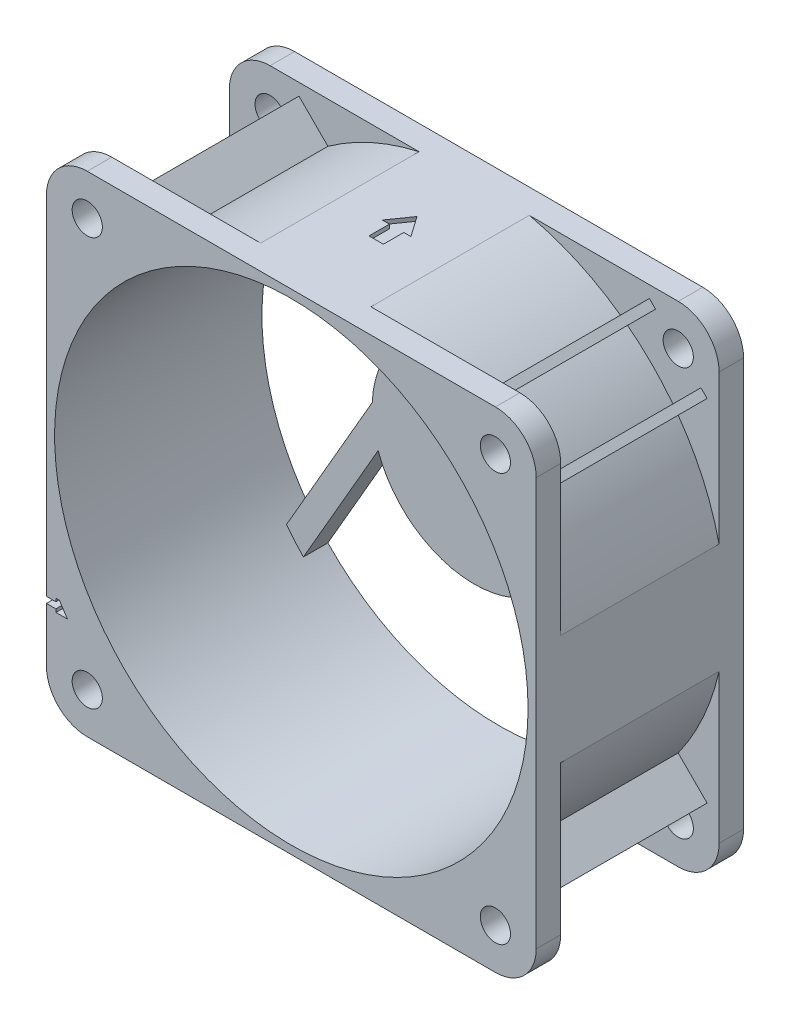
SolidWorks part; units mm, degrees
ref_plane "Front" through (0, 0, 0) normal (0, 0, 1) x (1, 0, 0)
ref_plane "Top" through (0, 0, 0) normal (0, 1, 0) x (1, 0, 0)
ref_plane "Right" through (0, 0, 0) normal (1, 0, 0) x (0, 0, -1)
sketch "Support-Front" plane through (0, 0, 0) normal (0, 0, 1) x (1, 0, 0)
  line L0 (-30, 0) -> (30, 0) construction
  line L1 (0, 30) -> (0, -30) construction
  line L2 (30, -25) -> (30, 25)
  line L3 (-30, -25) -> (-30, 25)
  line L4 (25, 30) -> (-25, 30)
  line L5 (25, -30) -> (-25, -30)
  line L6 (0, 30) -> (0, 40.3553) construction
  arc A0 (30, 25) -> (25, 30) centre (25, 25) ccw
  arc A1 (-30, 25) -> (-25, 30) centre (-25, 25) cw
  arc A2 (-30, -25) -> (-25, -30) centre (-25, -25) ccw
  arc A3 (30, -25) -> (25, -30) centre (25, -25) cw
  circle A4 centre (25, 25) radius 1.85
  circle A5 centre (-25, 25) radius 1.85
  circle A6 centre (-25, -25) radius 1.85
  circle A7 centre (25, -25) radius 1.85
  circle A8 centre (0, 0) radius 29
  circle A9 centre (0, 0) radius 12.5
  circle A10 centre (0, 0) radius 30
  circle A11 centre (0, 0) radius 40.3553 construction
  dimension "Diam-Fixing-Hole" = 3.7
  dimension "Diam-Fan-Hole" = 58
  dimension "Diam-Fixing-Plate-Fan" = 25
  dimension "Width" = 60
  dimension "Dist-Fixing-Hole" = 50
sketch "Support-Right" plane through (0, 0, 0) normal (1, 0, 0) x (0, 0, -1)
  line L0 (-25.4, 0) -> (0, 0) construction
  line L1 (-12.7, 30) -> (-12.7, -30) construction
  line L2 (-3, 30) -> (-3, -30)
  line L3 (-25.4, 30) -> (0, 30)
  line L4 (-25.4, 30) -> (-25.4, -30)
  line L5 (-25.4, -30) -> (0, -30)
  line L6 (0, 30) -> (0, -30)
  line L7 (-22.4, 30) -> (-22.4, -30)
  line L8 (-12.7, 30) -> (-12.7, 31.5) construction
  line L9 (0, 0) -> (-1.5, 0) construction
  line L10 (-1.5, 0) -> (-3, 0) construction
  dimension "Thickness" = 25.4
sketch "Support-Front-Reinforcment-Place" plane through (0, 0, 0) normal (0, 0, 1) x (1, 0, 0)
  line L0 (0, 30) -> (0, 0) construction
  line L1 (0, 29) -> (0, 30) construction
  line L2 (9.459, 30) -> (9.9454, 27.2413)
  line L3 (25, 30) -> (-25, 30) construction
  line L4 (-9.459, 30) -> (-9.9454, 27.2413)
  line L5 (9.459, 30) -> (0, 0) construction
  line L6 (-9.459, 30) -> (0, 0) construction
  line L7 (9.459, 30) -> (-9.459, 30)
  circle A3 centre (0, 0) radius 29 construction
  arc A4 (9.9454, 27.2413) -> (-9.9454, 27.2413) centre (0, 0) ccw
  point P10 (0, 29.5)
  dimension "D1" = 20
  dimension "D2" = 35
sketch "Support-Front-Reinforcment-Strip" plane through (0, 0, 0) normal (0, 0, 1) x (1, 0, 0)
  line L0 (17.381, 24.452) -> (21.4645, 28.5355)
  line L1 (24.452, 17.381) -> (28.5355, 21.4645)
  line L2 (25, 25) -> (0, 0) construction
  line L3 (28.5355, 21.4645) -> (27.7796, 22.2204)
  line L4 (21.4645, 28.5355) -> (22.2204, 27.7796)
  line L5 (27.7796, 22.2204) -> (23.8099, 18.2507)
  line L6 (22.2204, 27.7796) -> (18.2507, 23.8099)
  line L7 (25, 25) -> (23.8099, 18.2507) construction
  line L8 (25, 25) -> (18.2507, 23.8099) construction
  line L9 (29.2915, 20.7085) -> (25.8374, 17.2544)
  line L10 (20.7085, 29.2915) -> (17.2544, 25.8374)
  line L11 (29.2915, 20.7085) -> (29.2915, 10.3584)
  line L12 (20.7085, 29.2915) -> (10.3584, 29.2915)
  line L13 (28.5355, 21.4645) -> (29.2915, 20.7085) construction
  line L14 (21.4645, 28.5355) -> (20.7085, 29.2915) construction
  line L15 (21.9691, 21.9691) -> (21.2132, 21.2132) construction
  line L16 (20.7085, 29.2915) -> (22.2204, 27.7796) construction
  line L17 (-28.8419, -17.5957) -> (-30, -17.5957)
  line L18 (-30, -25) -> (-30, 25) construction
  line L19 (-28.8419, -17.2194) -> (-28.8419, -17.5957)
  line L20 (-28.8419, -17.2194) -> (-28.3997, -17.2194)
  line L21 (-27.4306, -18.7246) -> (-28.8419, -18.7246)
  line L22 (-28.8419, -18.3483) -> (-30, -18.3483)
  line L23 (-28.8419, -18.3483) -> (-28.8419, -18.7246)
  line L24 (-28.8419, -18.3483) -> (-27.6837, -18.3483) construction
  line L25 (-30, -17.972) -> (-25.3435, -17.972) construction
  line L26 (-27.6717, -17.972) -> (-27.6717, -17.5957) construction
  line L27 (-27.6717, -17.972) -> (-27.6717, -18.3483) construction
  line L28 (-28.8419, -18.3483) -> (-30, -17.972) construction
  line L29 (-25, -25) -> (-30, -25) construction
  line L30 (-27.5, -17.972) -> (-27.5, -21.486) construction
  line L31 (-27.5, -17.972) -> (-27.5, -14.458) construction
  line L32 (-27.5, -21.486) -> (-27.5, -25) construction
  line L33 (-25, -25) -> (-23.4846, -23.4846) construction
  line L34 (-23.4846, -23.4846) -> (-21.9691, -21.9691) construction
  arc A0 (21.4645, 28.5355) -> (28.5355, 21.4645) centre (25, 25) cw
  arc A1 (30, 25) -> (25, 30) centre (25, 25) ccw construction
  circle A2 centre (0, 0) radius 31.069
  circle A3 centre (0, 0) radius 30 construction
  circle A4 centre (0, 0) radius 33.2122 construction
  arc A6 (24.452, 17.381) -> (17.381, 24.452) centre (0, 0) ccw
  dimension "D1" = 35
  dimension "D2" = 45
  dimension "D3" = 18
  dimension "D4" = 45
sketch "Support-Front-Bone" plane through (0, 0, 0) normal (0, 0, 1) x (1, 0, 0)
  line L0 (-12.3101, -2.1706) -> (-21.9794, -18.9184) construction
  line L1 (-12.4892, 0.5192) -> (-22.9926, -17.6732)
  line L2 (-11.7643, -4.2252) -> (-20.9201, -20.0836)
  line L3 (0, 0) -> (0, 30) construction
  line L4 (25, 30) -> (-25, 30) construction
  line L6 (0, 0) -> (-12.3101, -2.1706) construction
  circle A0 centre (0, 0) radius 29 construction
  circle A1 centre (0, 0) radius 12.5 construction
  arc A2 (-12.4892, 0.5192) -> (-11.7643, -4.2252) centre (0, 0) ccw
  arc A3 (-22.9926, -17.6732) -> (-20.9201, -20.0836) centre (0, 0) ccw
  dimension "Angle-Bone" = 210
  dimension "Angle-Place-Bone" = 260
sketch "Support-Air-Exhaust" plane through (0, 0, 0) normal (0, 1, 0) x (1, 0, 0)
  line L0 (0, 0) -> (0, -10) construction
  line L1 (0, -10) -> (0, -12.5) construction
  line L2 (0, -12.5) -> (0, -15) construction
  line L3 (0, -15) -> (0, -10) construction
  line L4 (0, -10) -> (-1.7505, -12.5)
  line L5 (-1.7505, -12.5) -> (-0.8816, -12.5)
  line L6 (-0.8816, -12.5) -> (-0.8816, -15)
  line L7 (0.8816, -15) -> (-0.8816, -15)
  line L8 (0, -10) -> (-0.8816, -15) construction
  line L9 (-0.8816, -12.5) -> (0, -12.5) construction
  line L10 (0.8816, -12.5) -> (0.8816, -15)
  line L11 (1.7505, -12.5) -> (0.8816, -12.5)
  line L12 (0, -10) -> (1.7505, -12.5)
  dimension "D1" = 10
  dimension "D2" = 5
  dimension "D3" = 35
  dimension "D4" = 10
ref_plane "Plane1" through (0, 0, 25.4) normal (0, 0, 1) x (1, 0, 0)
ref_plane "Plane2" through (0, 29.5, 0) normal (0, 1, 0) x (-1, 0, 0)
sketch "Sketch-Body" plane through (0, 0, 0) normal (0, 0, 1) x (1, 0, 0)
  line L4 (-25, -30) -> (25, -30)
  line L5 (-30, 25) -> (-30, -25)
  line L6 (25, 30) -> (-25, 30)
  line L7 (30, -25) -> (30, 25)
  line L8 (-25, -30) -> (25, -30)
  line L9 (-30, 25) -> (-30, -25)
  line L10 (25, 30) -> (-25, 30)
  line L11 (30, -25) -> (30, 25)
  circle A0 centre (0, 0) radius 29 construction
  circle A1 centre (0, 0) radius 29
  arc A4 (-30, -25) -> (-25, -30) centre (-25, -25) ccw
  arc A5 (-25, 30) -> (-30, 25) centre (-25, 25) ccw
  arc A6 (30, 25) -> (25, 30) centre (25, 25) ccw
  arc A7 (25, -30) -> (30, -25) centre (25, -25) ccw
  arc A8 (-30, -25) -> (-25, -30) centre (-25, -25) ccw
  arc A9 (-25, 30) -> (-30, 25) centre (-25, 25) ccw
  arc A10 (30, 25) -> (25, 30) centre (25, 25) ccw
  arc A11 (25, -30) -> (30, -25) centre (25, -25) ccw
  dimension "D1" = 0
extrude "Body" add sketch "Sketch-Body" along normal up to surface (25.4 mm away) up to plane "Plane1"
sketch "Sketch-Cut-Body" plane through (0, 0, 0) normal (1, 0, 0) x (0, 0, -1)
  line L0 (-25.4, 0) -> (0, 0) construction
  line L1 (-25.4, 0) -> (0, 0) construction
  line L2 (-12.7, 30) -> (-12.7, 31.5) construction
  line L5 (-22.4, 30.75) -> (-22.4, 40.3553)
  line L6 (-22.4, 40.3553) -> (-3, 40.3553)
  line L7 (-22.4, 30.75) -> (-3, 30.75)
  line L9 (-3, 40.3553) -> (-3, 30.75)
  line L10 (-3, 30) -> (-3, -30) construction
  line L11 (-22.4, 30) -> (-22.4, -30) construction
  point P9 (-12.7, 30.75)
revolve "Cut-Body" cut sketch "Sketch-Cut-Body" angle 360 about L1
sketch "Sketch-Reinforcment-Strip" plane through (0, 0, 0) normal (0, 0, 1) x (1, 0, 0)
  line L0 (24.452, 17.381) -> (28.5355, 21.4645) construction
  line L1 (17.381, 24.452) -> (21.4645, 28.5355) construction
  line L2 (24.452, 17.381) -> (28.5355, 21.4645)
  line L3 (17.381, 24.452) -> (21.4645, 28.5355)
  line L4 (27.7796, 22.2204) -> (23.8099, 18.2507) construction
  line L5 (28.5355, 21.4645) -> (27.7796, 22.2204) construction
  line L6 (27.7796, 22.2204) -> (23.8099, 18.2507)
  line L7 (28.5355, 21.4645) -> (27.7796, 22.2204)
  line L8 (22.2204, 27.7796) -> (18.2507, 23.8099) construction
  line L9 (21.4645, 28.5355) -> (22.2204, 27.7796) construction
  line L10 (22.2204, 27.7796) -> (18.2507, 23.8099)
  line L11 (21.4645, 28.5355) -> (22.2204, 27.7796)
  circle A1 centre (0, 0) radius 30 construction
  arc A2 (18.2507, 23.8099) -> (17.381, 24.452) centre (0, 0) ccw
  arc A3 (24.452, 17.381) -> (23.8099, 18.2507) centre (0, 0) ccw
extrude "Reinforcment-Strip" add sketch "Sketch-Reinforcment-Strip" along normal up to surface (25.4 mm away) up to plane "Plane1"
pattern_circular "CirPattern-Reinforcment-Strip" count 4 over 360 about axis through (0, 0, 0) along (0, 0, 1) of "Reinforcment-Strip"
sketch "Sketch-Fixing-Hole" plane through (0, 0, 0) normal (0, 0, 1) x (1, 0, 0)
  circle A0 centre (25, 25) radius 1.85 construction
  circle A1 centre (25, 25) radius 1.85
extrude "Fixing-Hole" cut sketch "Sketch-Fixing-Hole" along normal through all
pattern_circular "CirPattern-Fixing-Hole" count 4 over 360 about axis through (0, 0, 0) along (0, 0, 1) of "Fixing-Hole"
sketch "Sketch-Bone" plane through (0, 0, 0) normal (0, 0, 1) x (1, 0, 0)
  line L0 (-11.7643, -4.2252) -> (-20.9201, -20.0836) construction
  line L1 (-12.4892, 0.5192) -> (-22.9926, -17.6732) construction
  line L2 (-11.7643, -4.2252) -> (-20.9201, -20.0836)
  line L3 (-12.4892, 0.5192) -> (-22.9926, -17.6732)
  circle A0 centre (0, 0) radius 29 construction
  circle A1 centre (0, 0) radius 12.5 construction
  arc A2 (-22.9926, -17.6732) -> (-20.9201, -20.0836) centre (0, 0) ccw
  arc A3 (-12.4892, 0.5192) -> (-11.7643, -4.2252) centre (0, 0) ccw
extrude "Bone" add sketch "Sketch-Bone" along normal blind 3
pattern_circular "CirPattern-Bone" count 3 over 360 about axis through (0, 0, 0) along (0, 0, 1) of "Bone"
sketch "Sketch1" plane through (0, 0, 25.4) normal (0, 0, 1) x (1, 0, 0)
  line L2 (-27.4306, -18.7246) -> (-28.8419, -18.7246) construction
  line L3 (-28.8419, -18.3483) -> (-28.8419, -18.7246) construction
  line L6 (-28.8419, -18.3483) -> (-30, -18.3483) construction
  line L7 (-30, -25) -> (-30, 25) construction
  line L8 (-28.8419, -17.5957) -> (-30, -17.5957) construction
  line L9 (-28.8419, -17.2194) -> (-28.8419, -17.5957) construction
  line L10 (-28.8419, -17.2194) -> (-28.3997, -17.2194) construction
  line L11 (-27.4306, -18.7246) -> (-28.8419, -18.7246)
  line L12 (-28.8419, -18.3483) -> (-28.8419, -18.7246)
  line L13 (-28.8419, -18.3483) -> (-30, -18.3483)
  line L14 (-30, -18.3483) -> (-30, -17.5957)
  line L15 (-28.8419, -17.5957) -> (-30, -17.5957)
  line L16 (-28.8419, -17.2194) -> (-28.8419, -17.5957)
  line L17 (-28.8419, -17.2194) -> (-28.3997, -17.2194)
  circle A3 centre (0, 0) radius 33.2122 construction
  arc A5 (-28.3997, -17.2194) -> (-27.4306, -18.7246) centre (0, 0) ccw
extrude "Cut-Reinforcment-Strip-Hole" cut sketch "Sketch1" against normal up to surface (22.4 mm away) up to face at (23.318, 23.318, 3)
pattern_circular "CirPattern1" [suppressed] count 4 over 360
sketch "Sketch-Fixing-Plate-Fan" plane through (0, 0, 0) normal (0, 0, 1) x (1, 0, 0)
  circle A0 centre (0, 0) radius 12.5 construction
  circle A1 centre (0, 0) radius 12.5
extrude "Fixing-Plate-Fan" add sketch "Sketch-Fixing-Plate-Fan" along normal blind 3
sketch "Sketch4" plane through (0, 29.5, 0) normal (0, 1, 0) x (-1, 0, 0)
  line L7 (0.8816, 15) -> (-0.8816, 15)
  line L8 (0.8816, 12.5) -> (0.8816, 15)
  line L9 (1.7505, 12.5) -> (0.8816, 12.5)
  line L10 (0, 10) -> (1.7505, 12.5)
  line L11 (-1.7505, 12.5) -> (0, 10)
  line L12 (-0.8816, 12.5) -> (-1.7505, 12.5)
  line L13 (-0.8816, 15) -> (-0.8816, 12.5)
  line L14 (0.8816, 15) -> (-0.8816, 15)
  line L15 (0.8816, 12.5) -> (0.8816, 15)
  line L16 (1.7505, 12.5) -> (0.8816, 12.5)
  line L17 (0, 10) -> (1.7505, 12.5)
  line L18 (-1.7505, 12.5) -> (0, 10)
  line L19 (-0.8816, 12.5) -> (-1.7505, 12.5)
  line L20 (-0.8816, 15) -> (-0.8816, 12.5)
  dimension "D1" = 0
extrude "Air-Exhaust" cut sketch "Sketch4" along normal through all
equation "\"Diam-Fan-Hole@Support-Front\" = \"Width@Support-Front\"-2"
